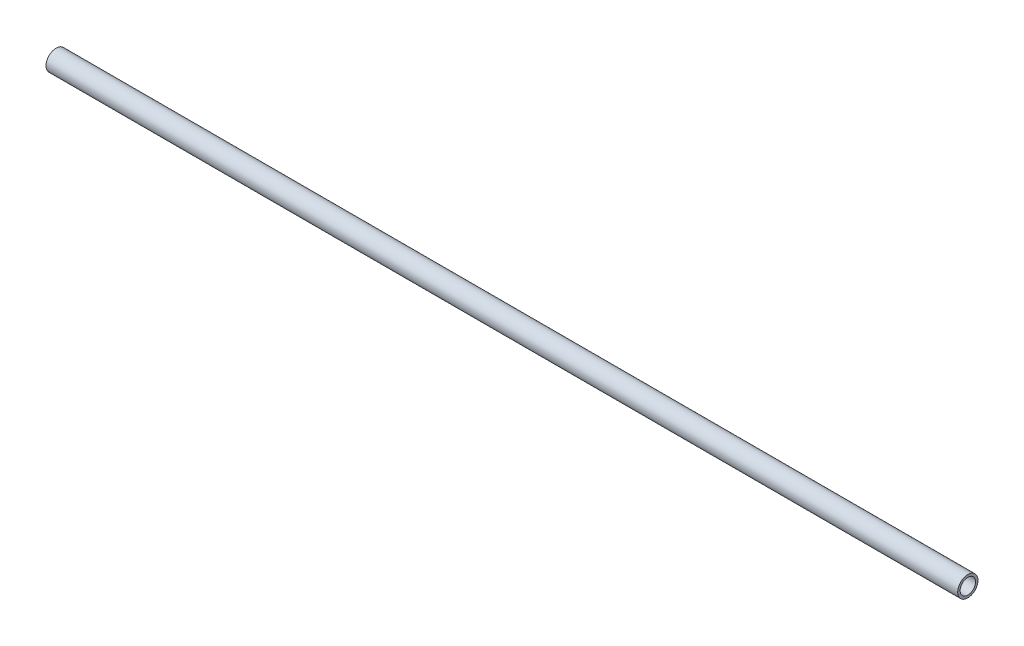
SolidWorks part; units mm, degrees
material "AISI 4130 Steel, annealed at 865C"
ref_plane "Front Plane" through (0, 0, 0) normal (0, 0, 1) x (1, 0, 0)
ref_plane "Top Plane" through (0, 0, 0) normal (0, 1, 0) x (1, 0, 0)
ref_plane "Right Plane" through (0, 0, 0) normal (1, 0, 0) x (0, 0, -1)
sketch "Sketch1" plane through (0, 0, 0) normal (1, 0, 0) x (0, 0, -1)
  circle A0 centre (0, 0) radius 12.7
  circle A1 centre (0, 0) radius 9.652
  dimension "D1" = 25.4
  dimension "D2" = 19.304
extrude "Boss-Extrude1" add sketch "Sketch1" along normal blind 1140
